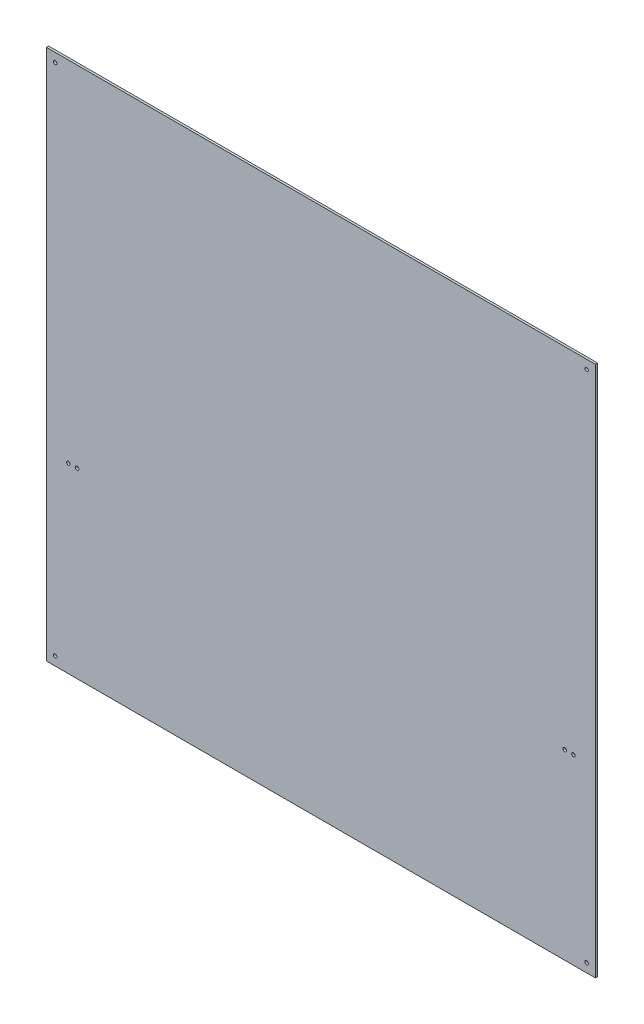
SolidWorks part; units mm, degrees
ref_plane "前视基准面" through (0, 0, 0) normal (0, 0, 1) x (1, 0, 0)
ref_plane "上视基准面" through (0, 0, 0) normal (0, 1, 0) x (1, 0, 0)
ref_plane "右视基准面" through (0, 0, 0) normal (1, 0, 0) x (0, 0, -1)
sketch "草图1" plane through (0, 0, 0) normal (0, 0, 1) x (1, 0, 0)
  line L1 (-653.5664, 554.6726) -> (596.4336, 554.6726)
  line L2 (-653.5664, 554.6726) -> (-653.5664, -655.3274)
  line L3 (-653.5664, -655.3274) -> (596.4336, -655.3274)
  line L4 (596.4336, 554.6726) -> (596.4336, -655.3274)
  dimension "D1" = 1250
  dimension "D2" = 1210
extrude "凸台-拉伸1" add sketch "草图1" along normal blind 5 contours L1 L4 L3 L2
sketch "草图2" plane through (0, 0, 5) normal (0, 0, 1) x (1, 0, 0)
  line L0 (-653.5664, 554.6726) -> (596.4336, 554.6726) construction
  line L2 (-653.5664, 554.6726) -> (-653.5664, -655.3274) construction
  circle A0 centre (-633.5664, 534.6726) radius 4.05
  circle A1 centre (576.4336, 534.6726) radius 4.05
  circle A2 centre (576.4336, -635.3274) radius 4.05
  circle A3 centre (-633.5664, -635.3274) radius 4.05
  dimension "D1" = 20
  dimension "D2" = 20
  dimension "D3" = 2
  dimension "D4" = 2
extrude "切除-拉伸1" cut sketch "草图2" against normal blind 5
sketch "草图3" plane through (0, 0, 5) normal (0, 0, 1) x (1, 0, 0)
  line L0 (-653.5664, 554.6726) -> (-653.5664, -655.3274) construction
  line L1 (-653.5664, -655.3274) -> (596.4336, -655.3274) construction
  line L2 (596.4336, 554.6726) -> (596.4336, -655.3274) construction
  circle A0 centre (-603.5664, -240.3274) radius 4.05
  circle A1 centre (526.4336, -240.3274) radius 4.05
  circle A2 centre (-583.5664, -240.3274) radius 4.05
  circle A3 centre (546.4336, -240.3274) radius 4.05
  dimension "D1" = 50
  dimension "D2" = 415
  dimension "D3" = 50
  dimension "D5" = 20
  dimension "D6" = 415
  dimension "D4" = 2
extrude "切除-拉伸2" cut sketch "草图3" against normal blind 5
